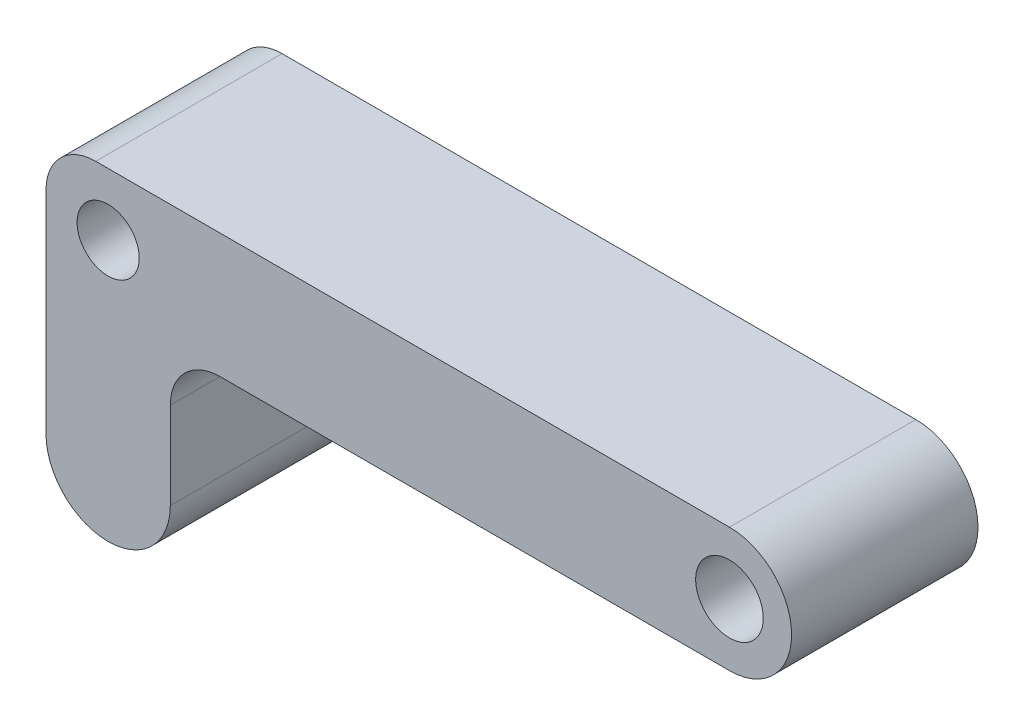
SolidWorks part; units mm, degrees
material "6061 Alloy"
ref_plane "Front Plane" through (0, 0, 0) normal (0, 0, 1) x (1, 0, 0)
ref_plane "Top Plane" through (0, 0, 0) normal (0, 1, 0) x (1, 0, 0)
ref_plane "Right Plane" through (0, 0, 0) normal (1, 0, 0) x (0, 0, -1)
sketch "Sketch1" plane through (0, 0, 0) normal (0, 0, 1) x (1, 0, 0)
  line L0 (0, 10.16) -> (31.75, 10.16) construction
  line L1 (0, 10.16) -> (0, 0) construction
  line L2 (3.175, 6.985) -> (3.175, 0)
  line L3 (3.175, 6.985) -> (31.75, 6.985)
  line L4 (-3.175, 13.335) -> (-3.175, 0)
  line L5 (-3.175, 13.335) -> (31.75, 13.335)
  arc A0 (31.75, 13.335) -> (31.75, 6.985) centre (31.75, 10.16) cw
  arc A1 (3.175, 0) -> (-3.175, 0) centre (0, 0) cw
  dimension "D1" = 10.16
  dimension "D2" = 31.75
  dimension "D3" = 90
  dimension "D4" = 3.175
  dimension "D5" = 3.175
extrude "Boss-Extrude1" add sketch "Sketch1" along normal blind 9.525
fillet "Fillet1" radius 2.54 2 edges at (-3.175, 13.335, 4.7625) (3.175, 6.985, 4.7625)
sketch "Sketch5" plane through (0, 0, 9.525) normal (0, 0, 1) x (1, 0, 0)
  circle A0 centre (0, 10.16) radius 1.5875
  dimension "D1" = 3.175
  dimension "D2" = 10.16
extrude "Cut-Extrude1" cut sketch "Sketch5" against normal through all
hole_wizard "#8-32 Tapped Hole1" positions "Sketch8" profile "Sketch9" tap size "#8-32" standard "Ansi Inch" end condition through all
sketch "Sketch8" plane through (0, 0, 9.525) normal (0, 0, 1) x (1, 0, 0)
  point P1 (31.75, 10.16)
sketch "Sketch9" plane through (31.75, 10.16, 9.525) normal (1, 0, 0) x (0, -1, 0)
  line L0 (0, 0) -> (0, 9.525)
  line L1 (0, 9.525) -> (1.7272, 9.525)
  line L2 (1.7272, 9.525) -> (1.7272, 0)
  line L5 (1.7272, 0) -> (0, 0)
  line L11 (0, -6.35) -> (0, 107.95) construction
  dimension "Thread Major Dia." = 3.4544
  dimension "Thru Tap Drill Depth" = 9.525
